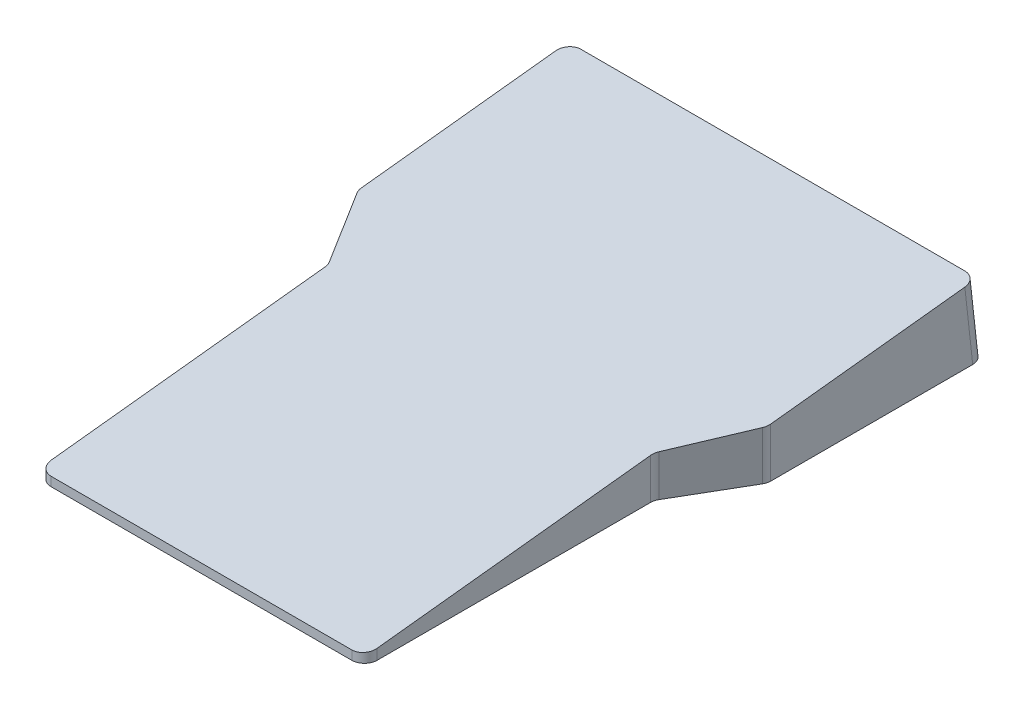
SolidWorks part; units mm, degrees
ref_plane "Front Plane" through (0, 0, 0) normal (0, 0, 1) x (1, 0, 0)
ref_plane "Top Plane" through (0, 0, 0) normal (0, 1, 0) x (1, 0, 0)
ref_plane "Right Plane" through (0, 0, 0) normal (1, 0, 0) x (0, 0, -1)
sketch "Sketch1" plane through (0, 0, 0) normal (0, 1, 0) x (1, 0, 0)
  line L0 (-57.5973, -8.4441) -> (-46.0973, -28.1941)
  line L1 (-46.0973, 51.8059) -> (43.9027, 51.8059)
  line L2 (-46.0973, 51.8059) -> (-46.0973, -108.1941)
  line L3 (-46.0973, -108.1941) -> (43.9027, -108.1941)
  line L4 (43.9027, 51.8059) -> (43.9027, -108.1941)
  line L5 (-57.5973, 51.8059) -> (55.4027, 51.8059)
  line L6 (-57.5973, 51.8059) -> (-57.5973, -8.4441)
  line L7 (-57.5973, -8.4441) -> (55.4027, -8.4441)
  line L8 (55.4027, 51.8059) -> (55.4027, -8.4441)
  line L9 (-57.5973, -8.4441) -> (-46.0973, -8.4441)
  line L10 (-46.0973, -8.4441) -> (-46.0973, -28.1941)
  line L11 (43.9027, -28.1941) -> (43.9027, -8.4441)
  line L12 (43.9027, -8.4441) -> (55.4027, -8.4441)
  line L13 (43.9027, -28.1941) -> (55.4027, -8.4441)
  point P12 (-1.0973, 51.8059)
  point P13 (-1.0973, 51.8059)
  dimension "D1" = 90
  dimension "D2" = 160
  dimension "D3" = 99.75
  dimension "D4" = 113
extrude "Boss-Extrude1" add sketch "Sketch1" along normal blind 20 contours L8 L5 L4 L7 | L2 L7 L4 L1 | L6 L7 L2 L5 | L7 L0 L2 | L7 L2 L3 L4 | L4 L13 L7
sketch "Sketch2" plane through (0, 0, 0) normal (0, -1, 0) x (1, 0, 0)
  line L3 (-57.5973, -51.8059) -> (55.4027, -51.8059) construction
  line L4 (-57.5973, -51.8059) -> (-57.5973, 8.4441) construction
  line L5 (55.4027, -51.8059) -> (55.4027, 8.4441) construction
  circle A2 centre (-51.0973, -45.3059) radius 2.4
  circle A3 centre (48.9027, -45.3059) radius 2.4
  circle A6 centre (47.4027, 6.9441) radius 2.35
  circle A7 centre (-49.5973, 6.9441) radius 2.35
  dimension "D5" = 4.8
  dimension "D6" = 4.8
  dimension "D16" = 21.25
  dimension "D18" = 4.7
  dimension "D19" = 4.7
  dimension "D2" = 8
  dimension "D3" = 21.25
  dimension "D4" = 8
  dimension "D7" = 6.5
  dimension "D8" = 6.5
  dimension "D9" = 6.5
  dimension "D10" = 6.5
extrude "Boss-Extrude2" add sketch "Sketch2" along normal blind 3
sketch "Sketch3" plane through (55.4027, 0, 0) normal (1, 0, 0) x (0, 0, -1)
  line L0 (-108.1941, 0) -> (-108.1941, 2.5)
  line L1 (-108.1941, 20) -> (-108.1941, 0) construction
  line L2 (-108.1941, 2.5) -> (49.5876, 20)
  line L3 (51.8059, 20) -> (-8.4441, 20) construction
  line L4 (49.5876, 20) -> (51.8059, 0)
  line L5 (51.8059, 0) -> (-108.1941, 0)
  line L6 (-108.1941, 20) -> (-108.1941, 2.5)
  line L7 (51.8059, 0) -> (51.8059, 20)
  line L8 (51.8059, 20) -> (49.5876, 20)
  line L9 (49.5876, 20) -> (-108.1941, 20)
  line M5 (51.8059, 0) -> (51.8059, 20)
  line M6 (51.8059, 20) -> (-8.4441, 20)
  line M7 (-8.4441, 20) -> (-8.4441, 0)
  dimension "D1" = 2.5
  dimension "D2" = 90
extrude "Cut-Extrude1" cut sketch "Sketch3" against normal through all contours L9 L6 L2 M7 | L2 M7 M6 | L4 M6 M5
fillet "Fillet1" radius 3.5 8 edges at (55.4027, 10, -50.6967) (-57.5973, 10, -50.6967) (-57.5973, 6.7818, 8.4441) (-46.0973, 5.6865, 28.1941) (-46.0973, 1.25, 108.1941) (43.9027, 1.25, 108.1941) (43.9027, 5.6865, 28.1941) (55.4027, 6.7818, 8.4441)
